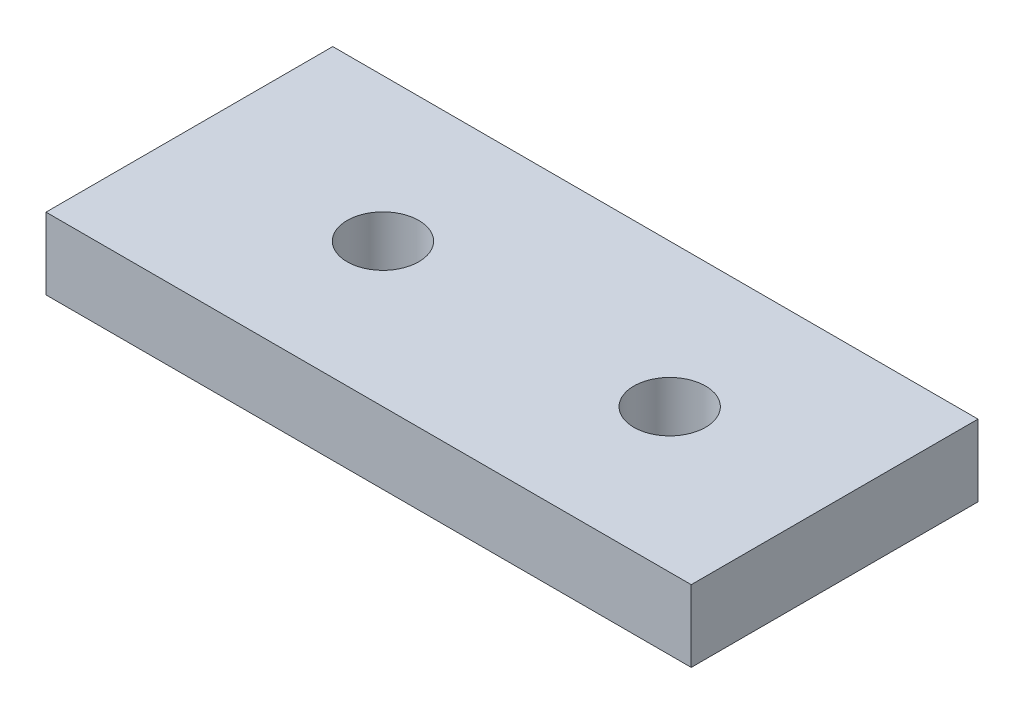
SolidWorks part; units mm, degrees
ref_plane "Płaszczyzna przednia" through (0, 0, 0) normal (0, 0, 1) x (1, 0, 0)
ref_plane "Płaszczyzna górna" through (0, 0, 0) normal (0, 1, 0) x (1, 0, 0)
ref_plane "Płaszczyzna prawa" through (0, 0, 0) normal (1, 0, 0) x (0, 0, -1)
sketch "Szkic1" plane through (0, 0, 0) normal (0, 1, 0) x (1, 0, 0)
  line L1 (0, 0) -> (90, 0)
  line L2 (0, 0) -> (0, 40)
  line L3 (0, 40) -> (90, 40)
  line L4 (90, 0) -> (90, 40)
  circle A0 centre (27, 20) radius 5
  circle A1 centre (67, 20) radius 5
  dimension "D3" = 10
  dimension "D4" = 20
  dimension "D5" = 27
  dimension "D1" = 90
  dimension "D2" = 40
  dimension "D6" = 2
extrude "Dodanie-wyciągnięcie1" add sketch "Szkic1" along normal blind 10
